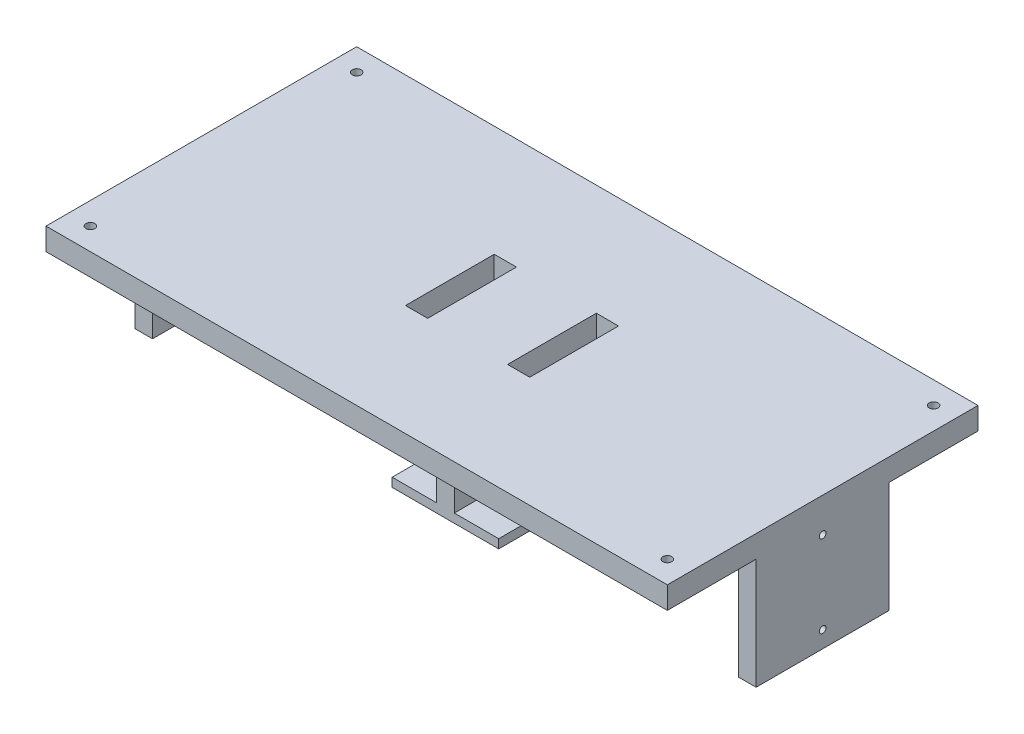
SolidWorks part; units mm, degrees
ref_plane "Płaszczyzna przednia" through (0, 0, 0) normal (0, 0, 1) x (1, 0, 0)
ref_plane "Płaszczyzna górna" through (0, 0, 0) normal (0, 1, 0) x (1, 0, 0)
ref_plane "Płaszczyzna prawa" through (0, 0, 0) normal (1, 0, 0) x (0, 0, -1)
sketch "Szkic1" plane through (0, 0, 0) normal (0, 1, 0) x (1, 0, 0)
  line L1 (0, 0) -> (140, 0)
  line L2 (0, 0) -> (0, -70)
  line L3 (0, -70) -> (140, -70)
  line L4 (140, 0) -> (140, -70)
  dimension "D1" = 140
  dimension "D2" = 70
extrude "Dodanie-wyciągnięcie1" add sketch "Szkic1" along normal blind 5
sketch "Szkic2" plane through (0, 0, 0) normal (0, -1, 0) x (1, 0, 0)
  line L0 (0, 35) -> (140, 35) construction
  line L1 (0, 0) -> (0, 70) construction
  line L2 (140, 70) -> (140, 0) construction
  line L3 (70, 70) -> (70, 0) construction
  line L4 (0, 50) -> (4, 50)
  line L5 (0, 50) -> (0, 20)
  line L6 (0, 20) -> (4, 20)
  line L7 (4, 50) -> (4, 20)
  line L8 (0, 70) -> (140, 70) construction
  line L9 (140, 0) -> (0, 0) construction
  line L10 (140, 20) -> (136, 20)
  line L11 (136, 50) -> (136, 20)
  line L12 (140, 50) -> (136, 50)
  line L13 (140, 50) -> (140, 20)
  line L14 (72, 20) -> (72, 50)
  line L15 (72, 20) -> (68, 20)
  line L16 (70, 20) -> (70, 50)
  line L17 (72, 50) -> (68, 50)
  line L18 (68, 20) -> (68, 50)
  line M12 (0, 70) -> (0, 0)
  line M14 (140, 0) -> (140, 70)
  dimension "D1" = 15
  dimension "D2" = 4
  dimension "D3" = 2
extrude "Dodanie-wyciągnięcie2" add sketch "Szkic2" along normal blind 25 contours L7 L4 L6 M12 | L12 L11 L10 M14 | L18 L17 L14 L15
sketch "Szkic3" plane through (0, -25, 0) normal (0, -1, 0) x (1, 0, 0)
  line L0 (70, 50) -> (70, 20) construction
  line L1 (72, 50) -> (68, 50) construction
  line L2 (72, 20) -> (68, 20) construction
  line L3 (58, 20) -> (58, 50)
  line L4 (58, 20) -> (82, 20)
  line L5 (70, 20) -> (70, 50)
  line L6 (58, 50) -> (82, 50)
  line L7 (82, 20) -> (82, 50)
  line M6 (68, 20) -> (72, 20)
  line M7 (72, 20) -> (72, 50)
  line M8 (72, 50) -> (68, 50)
  line M9 (68, 50) -> (68, 20)
  dimension "D1" = 12
extrude "Dodanie-wyciągnięcie3" add sketch "Szkic3" along normal blind 2 contours L4 L7 L6 M7 | L6 L3 L4 M9 | L5 L4 M7 M8 | L5 M6 M8 M9
sketch "Szkic4" plane through (0, 0, 0) normal (-1, 0, 0) x (0, 0, 1)
  line L0 (35, 5) -> (35, -25) construction
  line L1 (0, 5) -> (70, 5) construction
  line L2 (50, -25) -> (20, -25) construction
  line L3 (20, 0) -> (50, 0) construction
  circle A0 centre (35, -2.75) radius 0.75
  circle A1 centre (35, -21.25) radius 0.75
  dimension "D1" = 1.5
  dimension "D2" = 1.5
  dimension "D3" = 3.75
  dimension "D4" = 2.75
extrude "Wytnij-wyciągnięcie1" cut sketch "Szkic4" against normal blind 12
sketch "Szkic5" plane through (140, 0, 0) normal (1, 0, 0) x (0, 0, -1)
  circle A0 centre (-35, -21.25) radius 0.75 construction
  circle A1 centre (-35, -2.75) radius 0.75 construction
  circle A2 centre (-35, -21.25) radius 0.75
  circle A3 centre (-35, -2.75) radius 0.75
extrude "Wytnij-wyciągnięcie2" cut sketch "Szkic5" against normal blind 12
sketch "Szkic6" plane through (0, 5, 0) normal (0, 1, 0) x (1, 0, 0)
  line L0 (70, 0) -> (70, -70) construction
  line L1 (140, 0) -> (0, 0) construction
  line L2 (0, -70) -> (140, -70) construction
  line L3 (0, -35) -> (140, -35) construction
  line L4 (0, 0) -> (0, -70) construction
  line L5 (140, -70) -> (140, 0) construction
  line L6 (61, -25) -> (56, -25)
  line L7 (79, -45) -> (84, -45)
  line L8 (79, -45) -> (79, -25)
  line L9 (79, -25) -> (84, -25)
  line L10 (84, -45) -> (84, -25)
  line L11 (79, -45) -> (84, -25) construction
  line L12 (79, -25) -> (84, -45) construction
  line L13 (56, -45) -> (56, -25)
  line L14 (61, -45) -> (56, -45)
  line L15 (61, -45) -> (61, -25)
  point P12 (81.5, -35)
  dimension "D1" = 20
  dimension "D2" = 5
  dimension "D3" = 9
extrude "Wytnij-wyciągnięcie3" cut sketch "Szkic6" against normal blind 12
sketch "Szkic8" plane through (0, 5, 0) normal (0, 1, 0) x (1, 0, 0)
  line L0 (70, 0) -> (70, -70) construction
  line L1 (140, 0) -> (0, 0) construction
  line L2 (0, -70) -> (140, -70) construction
  line L3 (140, -35) -> (0, -35) construction
  line L4 (140, -70) -> (140, 0) construction
  line L5 (0, 0) -> (0, -70) construction
  circle A0 centre (135, -65) radius 1
  circle A1 centre (135, -5) radius 1
  circle A2 centre (5, -5) radius 1
  circle A3 centre (5, -65) radius 1
  dimension "D1" = 2
  dimension "D2" = 5
  dimension "D3" = 5
extrude "Wytnij-wyciągnięcie4" cut sketch "Szkic8" against normal blind 12
